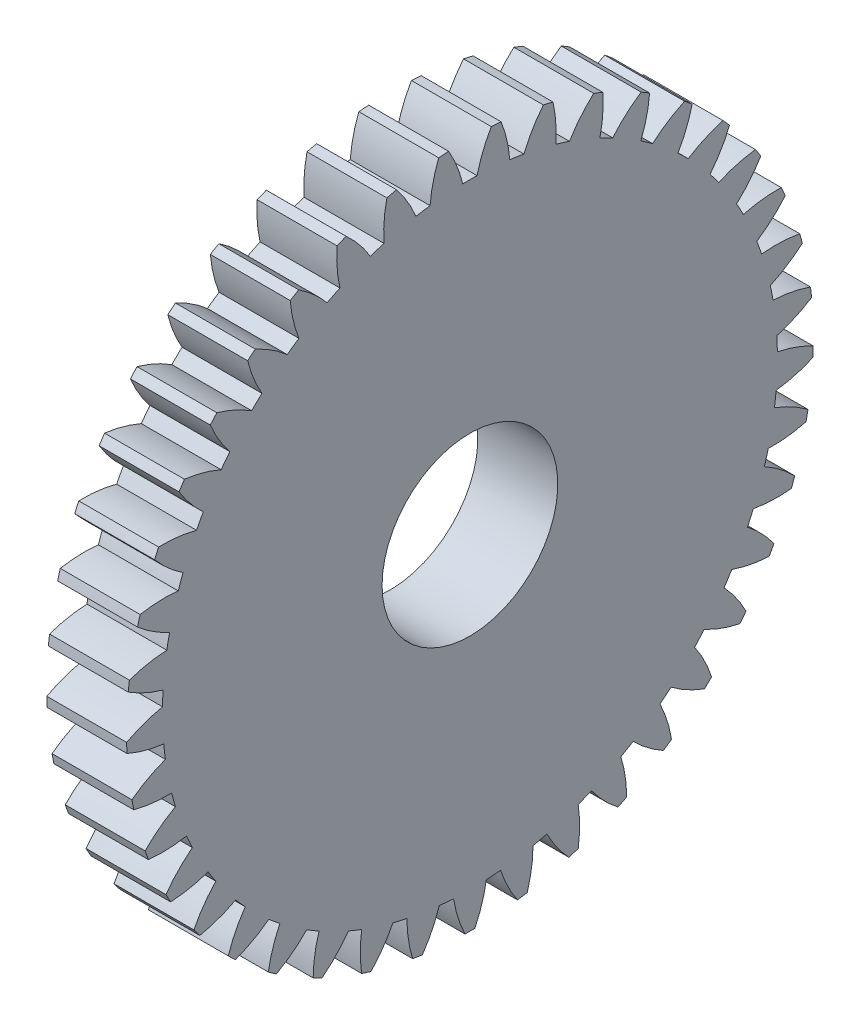
SolidWorks part; units mm, degrees
ref_plane "Front Plane" through (0, 0, 0) normal (0, 0, 1) x (1, 0, 0)
ref_plane "Top Plane" through (0, 0, 0) normal (0, 1, 0) x (1, 0, 0)
ref_plane "Right Plane" through (0, 0, 0) normal (1, 0, 0) x (0, 0, -1)
sketch "Sketch1" plane through (0, 0, 0) normal (1, 0, 0) x (0, 0, -1)
  circle A0 centre (0, 0) radius 5.5
  arc A1 (-21.3914, 2.1582) -> (-19.2125, 1.1841) centre (-16.9909, 9.0774) ccw
  arc A2 (-19.2125, 1.1841) -> (-19.2468, 0.2901) centre (0, 0) ccw
  arc A3 (-19.2468, 0.2901) -> (-21.4938, -0.5144) centre (-17.6359, -7.7501) ccw
  arc A4 (-21.4938, -0.5144) -> (-21.4702, -1.1325) centre (0, 0) ccw
  arc A5 (-21.4702, -1.1325) -> (-19.1681, -1.7626) centre (-18.1774, 6.3774) ccw
  arc A6 (-19.1681, -1.7626) -> (-19.0655, -2.6513) centre (0, 0) ccw
  arc A7 (-19.0655, -2.6513) -> (-21.1634, -3.7894) centre (-16.2462, -10.3514) ccw
  arc A8 (-21.1634, -3.7894) -> (-21.0457, -4.3966) centre (0, 0) ccw
  arc A9 (-21.0457, -4.3966) -> (-18.6744, -4.6679) centre (-18.9379, 3.5279) ccw
  arc A10 (-18.6744, -4.6679) -> (-18.4374, -5.5306) centre (0, 0) ccw
  arc A11 (-18.4374, -5.5306) -> (-20.337, -6.9755) centre (-14.4756, -12.7101) ccw
  arc A12 (-20.337, -6.9755) -> (-20.1279, -7.5577) centre (0, 0) ccw
  arc A13 (-20.1279, -7.5577) -> (-17.743, -7.4638) centre (-19.2545, 0.5957) ccw
  arc A14 (-17.743, -7.4638) -> (-17.377, -8.2802) centre (0, 0) ccw
  arc A15 (-17.377, -8.2802) -> (-19.0338, -9.9982) centre (-12.3658, -14.7708) ccw
  arc A16 (-19.0338, -9.9982) -> (-18.7383, -10.5416) centre (0, 0) ccw
  arc A17 (-18.7383, -10.5416) -> (-16.3957, -10.0848) centre (-19.1198, -2.3505) ccw
  arc A18 (-16.3957, -10.0848) -> (-15.9094, -10.8358) centre (0, 0) ccw
  arc A19 (-15.9094, -10.8358) -> (-17.2845, -12.7865) centre (-9.9661, -16.4853) ccw
  arc A20 (-17.2845, -12.7865) -> (-16.9095, -13.2785) centre (0, 0) ccw
  arc A21 (-16.9095, -13.2785) -> (-14.6642, -12.4694) centre (-18.5369, -5.2416) ccw
  arc A22 (-14.6642, -12.4694) -> (-14.0689, -13.1374) centre (0, 0) ccw
  arc A23 (-14.0689, -13.1374) -> (-15.1301, -15.2751) centre (-7.3329, -17.8135) ccw
  arc A24 (-15.1301, -15.2751) -> (-14.6844, -15.7041) centre (0, 0) ccw
  arc A25 (-14.6844, -15.7041) -> (-12.5888, -14.5618) centre (-17.5195, -8.0098) ccw
  arc A26 (-12.5888, -14.5618) -> (-11.8986, -15.131) centre (0, 0) ccw
  arc A27 (-11.8986, -15.131) -> (-12.621, -17.4057) centre (-4.5277, -18.724) ccw
  arc A28 (-12.621, -17.4057) -> (-12.1151, -17.7616) centre (0, 0) ccw
  arc A29 (-12.1151, -17.7616) -> (-10.2185, -16.3128) centre (-16.0915, -10.5903) ccw
  arc A30 (-10.2185, -16.3128) -> (-9.4494, -16.77) centre (0, 0) ccw
  arc A31 (-9.4494, -16.77) -> (-9.8162, -19.1283) centre (-1.6164, -19.1958) ccw
  arc A32 (-9.8162, -19.1283) -> (-9.2618, -19.4028) centre (0, 0) ccw
  arc A33 (-9.2618, -19.4028) -> (-7.6086, -17.6814) centre (-14.2863, -12.9225) ccw
  arc A34 (-7.6086, -17.6814) -> (-6.7787, -18.0159) centre (0, 0) ccw
  arc A35 (-6.7787, -18.0159) -> (-6.7812, -20.4026) centre (1.3327, -19.2175) ccw
  arc A36 (-6.7812, -20.4026) -> (-6.1915, -20.5892) centre (0, 0) ccw
  arc A37 (-6.1915, -20.5892) -> (-4.8203, -18.6357) centre (-12.1463, -14.9518) ccw
  arc A38 (-4.8203, -18.6357) -> (-3.9492, -18.8395) centre (0, 0) ccw
  arc A39 (-3.9492, -18.8395) -> (-3.5873, -21.1986) centre (4.2507, -18.7889) ccw
  arc A40 (-3.5873, -21.1986) -> (-2.976, -21.293) centre (0, 0) ccw
  arc A41 (-2.976, -21.293) -> (-1.9191, -19.1531) centre (-9.7216, -16.6307) ccw
  arc A42 (-1.9191, -19.1531) -> (-1.0271, -19.2216) centre (0, 0) ccw
  arc A43 (-1.0271, -19.2216) -> (-0.3093, -21.4978) centre (7.0689, -17.9198) ccw
  arc A44 (-0.3093, -21.4978) -> (0.3093, -21.4978) centre (0, 0) ccw
  arc A45 (0.3093, -21.4978) -> (1.0271, -19.2216) centre (-7.0689, -17.9198) ccw
  arc A46 (1.0271, -19.2216) -> (1.9191, -19.1531) centre (0, 0) ccw
  arc A47 (1.9191, -19.1531) -> (2.976, -21.293) centre (9.7216, -16.6307) ccw
  arc A48 (2.976, -21.293) -> (3.5873, -21.1986) centre (0, 0) ccw
  arc A49 (3.5873, -21.1986) -> (3.9492, -18.8395) centre (-4.2507, -18.7889) ccw
  arc A50 (3.9492, -18.8395) -> (4.8203, -18.6357) centre (0, 0) ccw
  arc A51 (4.8203, -18.6357) -> (6.1915, -20.5892) centre (12.1463, -14.9518) ccw
  arc A52 (6.1915, -20.5892) -> (6.7812, -20.4026) centre (0, 0) ccw
  arc A53 (6.7812, -20.4026) -> (6.7787, -18.0159) centre (-1.3327, -19.2175) ccw
  arc A54 (6.7787, -18.0159) -> (7.6086, -17.6814) centre (0, 0) ccw
  arc A55 (7.6086, -17.6814) -> (9.2618, -19.4028) centre (14.2863, -12.9225) ccw
  arc A56 (9.2618, -19.4028) -> (9.8162, -19.1283) centre (0, 0) ccw
  arc A57 (9.8162, -19.1283) -> (9.4494, -16.77) centre (1.6164, -19.1958) ccw
  arc A58 (9.4494, -16.77) -> (10.2185, -16.3128) centre (0, 0) ccw
  arc A59 (10.2185, -16.3128) -> (12.1151, -17.7616) centre (16.0915, -10.5903) ccw
  arc A60 (12.1151, -17.7616) -> (12.621, -17.4057) centre (0, 0) ccw
  arc A61 (12.621, -17.4057) -> (11.8986, -15.131) centre (4.5277, -18.724) ccw
  arc A62 (11.8986, -15.131) -> (12.5888, -14.5618) centre (0, 0) ccw
  arc A63 (12.5888, -14.5618) -> (14.6844, -15.7041) centre (17.5195, -8.0098) ccw
  arc A64 (14.6844, -15.7041) -> (15.1301, -15.2751) centre (0, 0) ccw
  arc A65 (15.1301, -15.2751) -> (14.0689, -13.1374) centre (7.3329, -17.8135) ccw
  arc A66 (14.0689, -13.1374) -> (14.6642, -12.4694) centre (0, 0) ccw
  arc A67 (14.6642, -12.4694) -> (16.9095, -13.2785) centre (18.5369, -5.2416) ccw
  arc A68 (16.9095, -13.2785) -> (17.2845, -12.7865) centre (0, 0) ccw
  arc A69 (17.2845, -12.7865) -> (15.9094, -10.8358) centre (9.9661, -16.4853) ccw
  arc A70 (15.9094, -10.8358) -> (16.3957, -10.0848) centre (0, 0) ccw
  arc A71 (16.3957, -10.0848) -> (18.7383, -10.5416) centre (19.1198, -2.3505) ccw
  arc A72 (18.7383, -10.5416) -> (19.0338, -9.9982) centre (0, 0) ccw
  arc A73 (19.0338, -9.9982) -> (17.377, -8.2802) centre (12.3658, -14.7708) ccw
  arc A74 (17.377, -8.2802) -> (17.743, -7.4638) centre (0, 0) ccw
  arc A75 (17.743, -7.4638) -> (20.1279, -7.5577) centre (19.2545, 0.5957) ccw
  arc A76 (20.1279, -7.5577) -> (20.337, -6.9755) centre (0, 0) ccw
  arc A77 (20.337, -6.9755) -> (18.4374, -5.5306) centre (14.4756, -12.7101) ccw
  arc A78 (18.4374, -5.5306) -> (18.6744, -4.6679) centre (0, 0) ccw
  arc A79 (18.6744, -4.6679) -> (21.0457, -4.3966) centre (18.9379, 3.5279) ccw
  arc A80 (21.0457, -4.3966) -> (21.1634, -3.7894) centre (0, 0) ccw
  arc A81 (21.1634, -3.7894) -> (19.0655, -2.6513) centre (16.2462, -10.3514) ccw
  arc A82 (19.0655, -2.6513) -> (19.1681, -1.7626) centre (0, 0) ccw
  arc A83 (19.1681, -1.7626) -> (21.4702, -1.1325) centre (18.1774, 6.3774) ccw
  arc A84 (21.4702, -1.1325) -> (21.4938, -0.5144) centre (0, 0) ccw
  arc A85 (21.4938, -0.5144) -> (19.2468, 0.2901) centre (17.6359, -7.7501) ccw
  arc A86 (19.2468, 0.2901) -> (19.2125, 1.1841) centre (0, 0) ccw
  arc A87 (19.2125, 1.1841) -> (21.3914, 2.1582) centre (16.9909, 9.0774) ccw
  arc A88 (21.3914, 2.1582) -> (21.3205, 2.7727) centre (0, 0) ccw
  arc A89 (21.3205, 2.7727) -> (18.977, 3.2247) centre (18.6123, -4.9672) ccw
  arc A90 (18.977, 3.2247) -> (18.8066, 4.103) centre (0, 0) ccw
  arc A91 (18.8066, 4.103) -> (20.8113, 5.3983) centre (15.4061, 11.5647) ccw
  arc A92 (20.8113, 5.3983) -> (20.6474, 5.9947) centre (0, 0) ccw
  arc A93 (20.6474, 5.9947) -> (18.2623, 6.0837) centre (19.1524, -2.0678) ccw
  arc A94 (18.2623, 6.0837) -> (17.9599, 6.9257) centre (0, 0) ccw
  arc A95 (17.9599, 6.9257) -> (19.7433, 8.5118) centre (13.4602, 13.7809) ccw
  arc A96 (19.7433, 8.5118) -> (19.4903, 9.0763) centre (0, 0) ccw
  arc A97 (19.4903, 9.0763) -> (17.1196, 8.8001) centre (19.2436, 0.88) ccw
  arc A98 (17.1196, 8.8001) -> (16.6922, 9.5861) centre (0, 0) ccw
  arc A99 (16.6922, 9.5861) -> (18.2126, 11.4259) centre (11.1988, 15.6741) ccw
  arc A100 (18.2126, 11.4259) -> (17.8764, 11.9451) centre (0, 0) ccw
  arc A101 (17.8764, 11.9451) -> (15.5757, 11.3103) centre (18.8837, 3.8072) ccw
  arc A102 (15.5757, 11.3103) -> (15.0333, 12.0219) centre (0, 0) ccw
  arc A103 (15.0333, 12.0219) -> (16.255, 14.0721) centre (8.6749, 17.1999) ccw
  arc A104 (16.255, 14.0721) -> (15.8435, 14.5339) centre (0, 0) ccw
  arc A105 (15.8435, 14.5339) -> (13.6666, 13.5554) centre (18.0813, 6.6452) ccw
  arc A106 (13.6666, 13.5554) -> (13.022, 14.1758) centre (0, 0) ccw
  arc A107 (13.022, 14.1758) -> (13.9164, 16.3885) centre (5.9477, 18.3225) ccw
  arc A108 (13.9164, 16.3885) -> (13.4392, 16.7821) centre (0, 0) ccw
  arc A109 (13.4392, 16.7821) -> (11.4372, 15.4827) centre (16.855, 9.3274) ccw
  arc A110 (11.4372, 15.4827) -> (10.7054, 15.9974) centre (0, 0) ccw
  arc A111 (10.7054, 15.9974) -> (11.2516, 18.3208) centre (3.0811, 19.0157) ccw
  arc A112 (11.2516, 18.3208) -> (10.7199, 18.6369) centre (0, 0) ccw
  arc A113 (10.7199, 18.6369) -> (8.9398, 17.0471) centre (15.2336, 11.791) ccw
  arc A114 (8.9398, 17.0471) -> (8.138, 17.4441) centre (0, 0) ccw
  arc A115 (8.138, 17.4441) -> (8.3231, 19.8236) centre (0.1423, 19.2632) ccw
  arc A116 (8.3231, 19.8236) -> (7.7494, 20.0549) centre (0, 0) ccw
  arc A117 (7.7494, 20.0549) -> (6.2327, 18.212) centre (13.2552, 13.9782) ccw
  arc A118 (6.2327, 18.212) -> (5.3798, 18.4819) centre (0, 0) ccw
  arc A119 (5.3798, 18.4819) -> (5.1995, 20.8618) centre (-2.7999, 19.0591) ccw
  arc A120 (5.1995, 20.8618) -> (4.5972, 21.0028) centre (0, 0) ccw
  arc A121 (4.5972, 21.0028) -> (3.3797, 18.95) centre (10.9661, 15.8378) ccw
  arc A122 (3.3797, 18.95) -> (2.4954, 19.0866) centre (0, 0) ccw
  arc A123 (2.4954, 19.0866) -> (1.954, 21.411) centre (-5.6765, 18.4084) ccw
  arc A124 (1.954, 21.411) -> (1.3373, 21.4584) centre (0, 0) ccw
  arc A125 (1.3373, 21.4584) -> (0.4473, 19.2438) centre (8.42, 17.3261) ccw
  arc A126 (0.4473, 19.2438) -> (-0.4473, 19.2438) centre (0, 0) ccw
  arc A127 (-0.4473, 19.2438) -> (-1.3373, 21.4584) centre (-8.42, 17.3261) ccw
  arc A128 (-1.3373, 21.4584) -> (-1.954, 21.411) centre (0, 0) ccw
  arc A129 (-1.954, 21.411) -> (-2.4954, 19.0866) centre (5.6765, 18.4084) ccw
  arc A130 (-2.4954, 19.0866) -> (-3.3797, 18.95) centre (0, 0) ccw
  arc A131 (-3.3797, 18.95) -> (-4.5972, 21.0028) centre (-10.9661, 15.8378) ccw
  arc A132 (-4.5972, 21.0028) -> (-5.1995, 20.8618) centre (0, 0) ccw
  arc A133 (-5.1995, 20.8618) -> (-5.3798, 18.4819) centre (2.7999, 19.0591) ccw
  arc A134 (-5.3798, 18.4819) -> (-6.2327, 18.212) centre (0, 0) ccw
  arc A135 (-6.2327, 18.212) -> (-7.7494, 20.0549) centre (-13.2552, 13.9782) ccw
  arc A136 (-7.7494, 20.0549) -> (-8.3231, 19.8236) centre (0, 0) ccw
  arc A137 (-8.3231, 19.8236) -> (-8.138, 17.4441) centre (-0.1423, 19.2632) ccw
  arc A138 (-8.138, 17.4441) -> (-8.9398, 17.0471) centre (0, 0) ccw
  arc A139 (-8.9398, 17.0471) -> (-10.7199, 18.6369) centre (-15.2336, 11.791) ccw
  arc A140 (-10.7199, 18.6369) -> (-11.2516, 18.3208) centre (0, 0) ccw
  arc A141 (-11.2516, 18.3208) -> (-10.7054, 15.9974) centre (-3.0811, 19.0157) ccw
  arc A142 (-10.7054, 15.9974) -> (-11.4372, 15.4827) centre (0, 0) ccw
  arc A143 (-11.4372, 15.4827) -> (-13.4392, 16.7821) centre (-16.855, 9.3274) ccw
  arc A144 (-13.4392, 16.7821) -> (-13.9164, 16.3885) centre (0, 0) ccw
  arc A145 (-13.9164, 16.3885) -> (-13.022, 14.1758) centre (-5.9477, 18.3225) ccw
  arc A146 (-13.022, 14.1758) -> (-13.6666, 13.5554) centre (0, 0) ccw
  arc A147 (-13.6666, 13.5554) -> (-15.8435, 14.5339) centre (-18.0813, 6.6452) ccw
  arc A148 (-15.8435, 14.5339) -> (-16.255, 14.0721) centre (0, 0) ccw
  arc A149 (-16.255, 14.0721) -> (-15.0333, 12.0219) centre (-8.6749, 17.1999) ccw
  arc A150 (-15.0333, 12.0219) -> (-15.5757, 11.3103) centre (0, 0) ccw
  arc A151 (-15.5757, 11.3103) -> (-17.8764, 11.9451) centre (-18.8837, 3.8072) ccw
  arc A152 (-17.8764, 11.9451) -> (-18.2126, 11.4259) centre (0, 0) ccw
  arc A153 (-18.2126, 11.4259) -> (-16.6922, 9.5861) centre (-11.1988, 15.6741) ccw
  arc A154 (-16.6922, 9.5861) -> (-17.1196, 8.8001) centre (0, 0) ccw
  arc A155 (-17.1196, 8.8001) -> (-19.4903, 9.0763) centre (-19.2436, 0.88) ccw
  arc A156 (-19.4903, 9.0763) -> (-19.7433, 8.5118) centre (0, 0) ccw
  arc A157 (-19.7433, 8.5118) -> (-17.9599, 6.9257) centre (-13.4602, 13.7809) ccw
  arc A158 (-17.9599, 6.9257) -> (-18.2623, 6.0837) centre (0, 0) ccw
  arc A159 (-18.2623, 6.0837) -> (-20.6474, 5.9947) centre (-19.1524, -2.0678) ccw
  arc A160 (-20.6474, 5.9947) -> (-20.8113, 5.3983) centre (0, 0) ccw
  arc A161 (-20.8113, 5.3983) -> (-18.8066, 4.103) centre (-15.4061, 11.5647) ccw
  arc A162 (-18.8066, 4.103) -> (-18.977, 3.2247) centre (0, 0) ccw
  arc A163 (-18.977, 3.2247) -> (-21.3205, 2.7727) centre (-18.6123, -4.9672) ccw
  arc A164 (-21.3205, 2.7727) -> (-21.3914, 2.1582) centre (0, 0) ccw
extrude "Boss-Extrude1" add sketch "Sketch1" against normal mid plane 5
